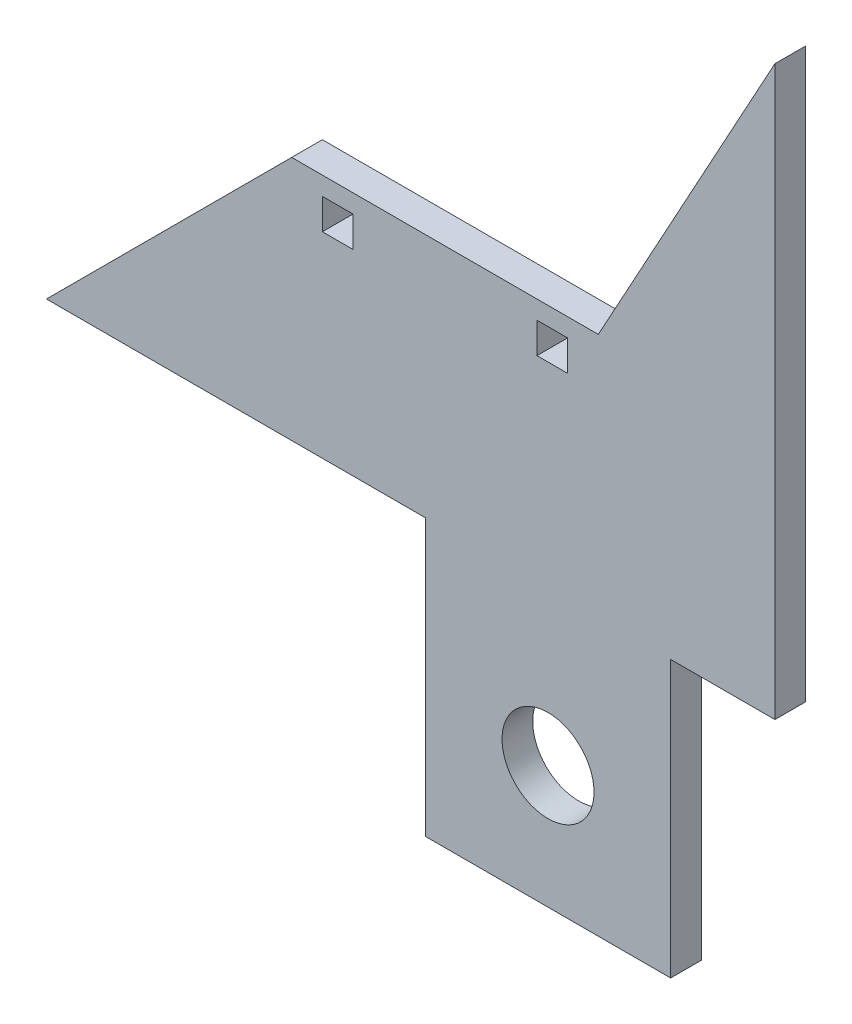
SolidWorks part; units mm, degrees
ref_plane "Front Plane" through (0, 0, 0) normal (0, 0, 1) x (1, 0, 0)
ref_plane "Top Plane" through (0, 0, 0) normal (0, 1, 0) x (1, 0, 0)
ref_plane "Right Plane" through (0, 0, 0) normal (1, 0, 0) x (0, 0, -1)
sketch "Sketch2" plane through (0, 0, 0) normal (0, 0, 1) x (1, 0, 0)
  line L1 (-61.8028, 20.6494) -> (-11.8028, 20.6494)
  line L2 (-11.8028, 20.6494) -> (17, 73.2839)
  line L3 (17, 73.2839) -> (17, -19.3506)
  line L4 (17, -19.3506) -> (0, -19.3506)
  line L5 (0, -19.3506) -> (0, -64.3506)
  line L6 (0, -64.3506) -> (-40, -64.3506)
  line L7 (-40, -64.3506) -> (-40, -19.3506)
  line L8 (-40, -19.3506) -> (-61.8028, -19.3506)
  line L9 (-61.8028, 20.6494) -> (-101.8028, -19.3506)
  line L10 (-101.8028, -19.3506) -> (-61.8028, -19.3506)
  dimension "D1" = 40
  dimension "D2" = 50
  dimension "D3" = 60
  dimension "D4" = 17
  dimension "D5" = 45
  dimension "D6" = 118.688
  dimension "D7" = 40
  dimension "D8" = 45
  dimension "D9" = 135
extrude "Boss-Extrude1" add sketch "Sketch2" along normal blind 5
sketch "Sketch3" plane through (0, 0, 5) normal (0, 0, 1) x (1, 0, 0)
  line L0 (-61.8028, 20.6494) -> (-61.8028, -19.3506) construction
  line L1 (-56.8028, 17.6494) -> (-51.8028, 17.6494)
  line L2 (-56.8028, 17.6494) -> (-56.8028, 12.6494)
  line L3 (-56.8028, 12.6494) -> (-51.8028, 12.6494)
  line L4 (-51.8028, 17.6494) -> (-51.8028, 12.6494)
  line L5 (-56.8028, 17.6494) -> (-51.8028, 12.6494) construction
  line L6 (-56.8028, 12.6494) -> (-51.8028, 17.6494) construction
  line L7 (-21.8028, 12.6494) -> (-16.8028, 12.6494)
  line L8 (-21.8028, 12.6494) -> (-21.8028, 17.6494)
  line L9 (-21.8028, 17.6494) -> (-16.8028, 17.6494)
  line L10 (-16.8028, 12.6494) -> (-16.8028, 17.6494)
  line L11 (-21.8028, 12.6494) -> (-16.8028, 17.6494) construction
  line L12 (-21.8028, 17.6494) -> (-16.8028, 12.6494) construction
  line L13 (-11.8028, 20.6494) -> (-61.8028, 20.6494) construction
  point P0 (-54.3028, 15.1494)
  point P5 (-19.3028, 15.1494)
  dimension "D1" = 5
  dimension "D2" = 5
  dimension "D3" = 5
  dimension "D4" = 3
  dimension "D5" = 5
extrude "Cut-Extrude1" cut sketch "Sketch3" against normal blind 5
sketch "Sketch4" plane through (0, 0, 5) normal (0, 0, 1) x (1, 0, 0)
  line L0 (-40, -64.3506) -> (0, -64.3506) construction
  circle A0 centre (-20, -44.3506) radius 7.5
  dimension "D1" = 15
  dimension "D2" = 20
extrude "Cut-Extrude2" cut sketch "Sketch4" against normal blind 10
